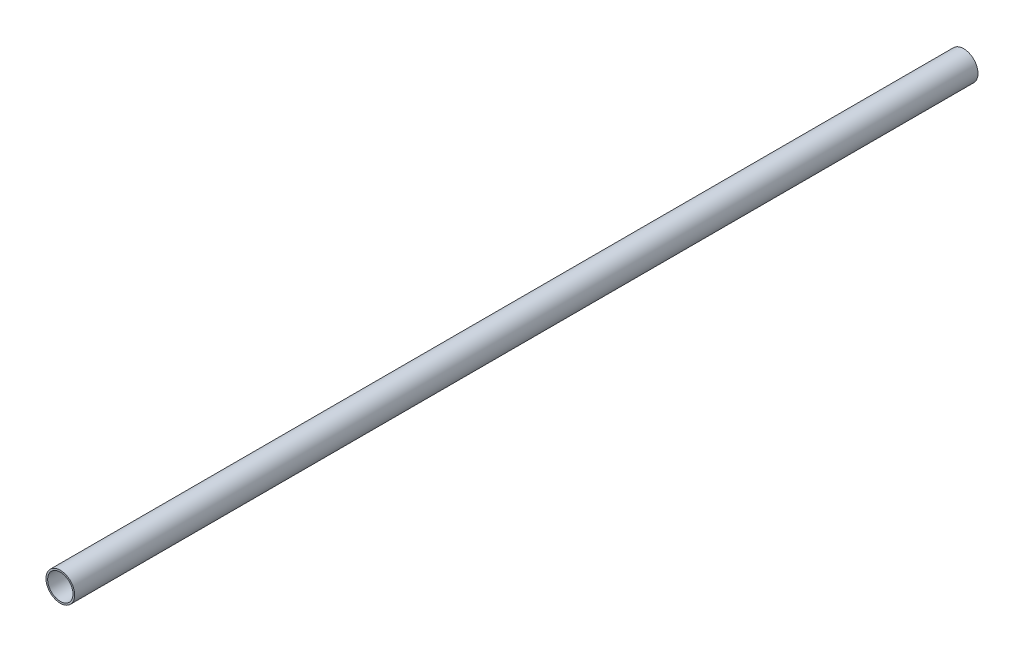
SolidWorks part; units mm, degrees
ref_plane "Front Plane" through (0, 0, 0) normal (0, 0, 1) x (1, 0, 0)
ref_plane "Top Plane" through (0, 0, 0) normal (0, 1, 0) x (1, 0, 0)
ref_plane "Right Plane" through (0, 0, 0) normal (1, 0, 0) x (0, 0, -1)
sketch "Sketch1" plane through (0, 0, 0) normal (0, 0, 1) x (1, 0, 0)
  circle A0 centre (0, 0) radius 12.7
  circle A1 centre (0, 0) radius 11.227
extrude "Boss-Extrude1" add sketch "Sketch1" along normal blind 800
